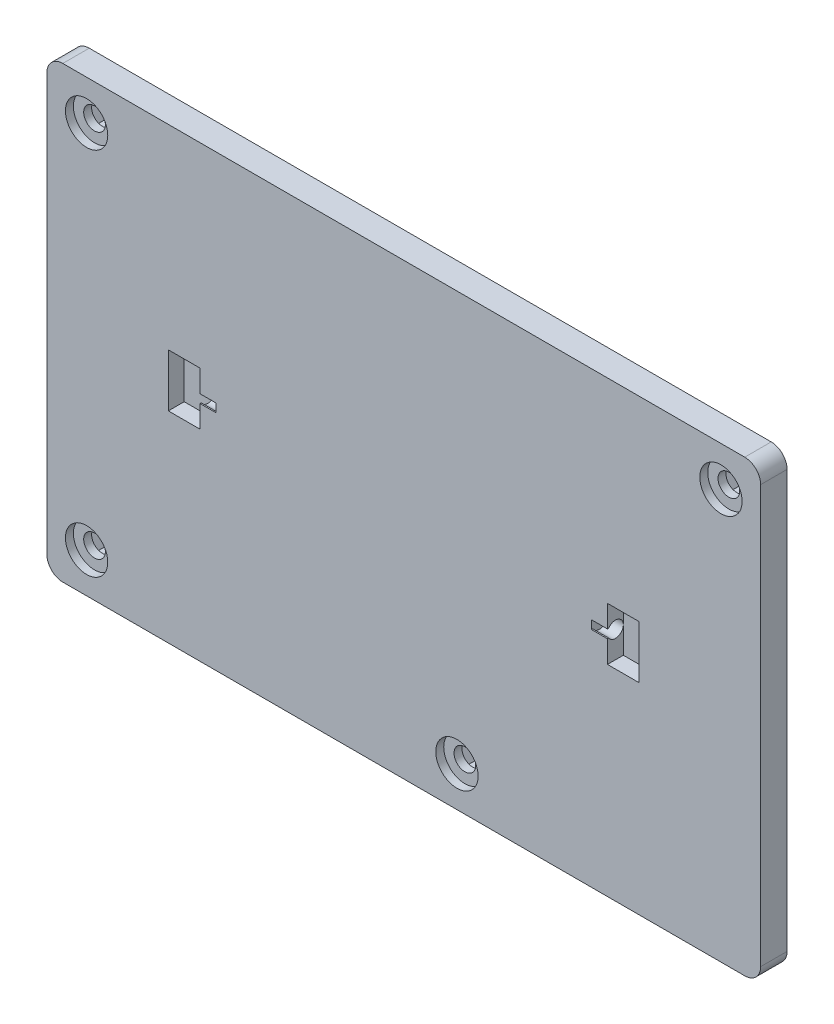
SolidWorks part; units mm, degrees
ref_plane "前视基准面" through (0, 0, 0) normal (0, 0, 1) x (1, 0, 0)
ref_plane "上视基准面" through (0, 0, 0) normal (0, 1, 0) x (1, 0, 0)
ref_plane "右视基准面" through (0, 0, 0) normal (1, 0, 0) x (0, 0, -1)
other "Configuration Table"
sketch "草图1" plane through (0, 0, 0) normal (0, 0, 1) x (1, 0, 0)
  line L1 (-64.45, 0) -> (64.45, 0)
  line L2 (-67.45, 3) -> (-67.45, 81.9)
  line L3 (-64.45, 84.9) -> (64.45, 84.9)
  line L4 (67.45, 3) -> (67.45, 81.9)
  arc A0 (-64.45, 0) -> (-67.45, 3) centre (-64.45, 3) cw
  arc A1 (64.45, 0) -> (67.45, 3) centre (64.45, 3) ccw
  arc A2 (64.45, 84.9) -> (67.45, 81.9) centre (64.45, 81.9) cw
  arc A3 (-67.45, 81.9) -> (-64.45, 84.9) centre (-64.45, 81.9) cw
  point P4 (0, 0)
  dimension "D1" = 3
extrude "凸台-拉伸1" add sketch "草图1" along normal blind 5
sketch "草图2" plane through (0, 0, 0) normal (0, 0, -1) x (-1, 0, 0)
  line L0 (-67.45, 3) -> (-67.45, 81.9) construction
  line L1 (-56.6591, 77.4) -> (-58.3046, 80.25)
  line L2 (-58.3046, 80.25) -> (-61.5954, 80.25)
  line L3 (-61.5954, 80.25) -> (-63.2409, 77.4)
  line L4 (-63.2409, 77.4) -> (-61.5954, 74.55)
  line L5 (-61.5954, 74.55) -> (-58.3046, 74.55)
  line L6 (-58.3046, 74.55) -> (-56.6591, 77.4)
  line L7 (-64.45, 84.9) -> (64.45, 84.9) construction
  line L8 (-67.45, 42.45) -> (67.45, 42.45) construction
  line L9 (67.45, 81.9) -> (67.45, 3) construction
  line L10 (0, 0) -> (0, 84.9) construction
  line L11 (64.45, 0) -> (-64.45, 0) construction
  line L12 (58.3046, 74.55) -> (56.6591, 77.4)
  line L13 (61.5954, 74.55) -> (58.3046, 74.55)
  line L14 (63.2409, 77.4) -> (61.5954, 74.55)
  line L15 (61.5954, 80.25) -> (63.2409, 77.4)
  line L16 (58.3046, 80.25) -> (61.5954, 80.25)
  line L17 (56.6591, 77.4) -> (58.3046, 80.25)
  line L30 (-13.3409, 7.5) -> (-11.6954, 4.65)
  line L31 (-11.6954, 4.65) -> (-8.4046, 4.65)
  line L32 (-8.4046, 4.65) -> (-6.7591, 7.5)
  line L33 (-6.7591, 7.5) -> (-8.4046, 10.35)
  line L34 (-8.4046, 10.35) -> (-11.6954, 10.35)
  line L35 (-11.6954, 10.35) -> (-13.3409, 7.5)
  line L36 (56.6591, 7.5) -> (58.3046, 4.65)
  line L37 (58.3046, 4.65) -> (61.5954, 4.65)
  line L38 (61.5954, 4.65) -> (63.2409, 7.5)
  line L39 (63.2409, 7.5) -> (61.5954, 10.35)
  line L40 (61.5954, 10.35) -> (58.3046, 10.35)
  line L41 (58.3046, 10.35) -> (56.6591, 7.5)
  circle A0 centre (-59.95, 77.4) radius 2.85 construction
  circle A3 centre (-10.05, 7.5) radius 2.85 construction
  circle A4 centre (59.95, 7.5) radius 2.85 construction
  dimension "D1" = 7.5
  dimension "D2" = 7.5
extrude "切除-拉伸1" cut sketch "草图2" against normal blind 2
sketch "草图3" plane through (0, 0, 2) normal (0, 0, -1) x (-1, 0, 0)
  line L0 (-61.5954, 80.25) -> (-58.3046, 74.55) construction
  line L1 (-56.6591, 77.4) -> (-59.95, 77.4) construction
  line L2 (-67.45, 42.45) -> (67.45, 42.45) construction
  line L3 (-67.45, 3) -> (-67.45, 81.9) construction
  line L4 (67.45, 81.9) -> (67.45, 3) construction
  line L5 (0, 84.9) -> (0, 0) construction
  line L6 (-64.45, 84.9) -> (64.45, 84.9) construction
  line L9 (-6.7591, 7.5) -> (-10.05, 7.5) construction
  line L10 (-8.4046, 10.35) -> (-11.6954, 4.65) construction
  circle A1 centre (-59.95, 77.4) radius 2.05
  circle A2 centre (59.95, 77.4) radius 2.05
  circle A6 centre (-10.05, 7.5) radius 2.05
  circle A7 centre (59.95, 7.5) radius 2.05
  dimension "D1" = 4.1
extrude "切除-拉伸2" cut sketch "草图3" against normal blind 3
sketch "草图4" plane through (0, 0, 5) normal (0, 0, 1) x (1, 0, 0)
  line L0 (-67.45, 81.9) -> (-67.45, 3) construction
  line L1 (-64.45, 0) -> (64.45, 0) construction
  line L2 (0, -8.4155) -> (0, 90.394) construction
  circle A0 centre (-59.95, 77.4) radius 4
  circle A1 centre (59.95, 77.4) radius 4
  circle A4 centre (-59.95, 7.5) radius 4
  circle A5 centre (10.05, 7.5) radius 4
  dimension "D1" = 8
  dimension "D2" = 8
  dimension "D3" = 8
  dimension "D4" = 8
  dimension "D5" = 70
  dimension "D6" = 7.5
  dimension "D7" = 7.5
  dimension "D8" = 7.5
extrude "切除-拉伸3" cut sketch "草图4" against normal blind 1.5
sketch "草图5" plane through (0, 0, 5) normal (0, 0, 1) x (1, 0, 0)
  line L0 (0, 84.9) -> (0, -9.6023) construction
  line L1 (-44.5, 48) -> (-38.5, 48)
  line L2 (-44.5, 48) -> (-44.5, 38)
  line L3 (-44.5, 38) -> (-38.5, 38)
  line L4 (-38.5, 48) -> (-38.5, 38)
  line L6 (-64.45, 0) -> (64.45, 0) construction
  line L7 (38.5, 48) -> (38.5, 38)
  line L8 (44.5, 38) -> (38.5, 38)
  line L9 (44.5, 48) -> (44.5, 38)
  line L10 (44.5, 48) -> (38.5, 48)
  dimension "D1" = 10
  dimension "D2" = 6
  dimension "D3" = 38.5
  dimension "D4" = 38
extrude "切除-拉伸4" cut sketch "草图5" against normal blind 3
sketch "草图6" plane through (38.5, 0, 0) normal (1, 0, 0) x (0, 0, -1)
  line L0 (-6.2696, 43) -> (0.482, 43) construction
  line L1 (-3.5, 48) -> (-3.5, 36.5367) construction
  line L2 (-4.7689, 43.8) -> (-5, 43.8)
  line L3 (-5, 42.2) -> (-5, 43.8)
  line L4 (-5, 48) -> (-5, 38)
  line L5 (-5, 38) -> (-2, 38)
  line L6 (-2, 38) -> (-2, 48)
  line L7 (-2, 48) -> (-5, 48)
  line L8 (-5, 48) -> (-5, 38) construction
  line L9 (-5, 38) -> (-2, 38) construction
  line L10 (-2, 38) -> (-2, 48) construction
  line L11 (-2, 48) -> (-5, 48) construction
  line L12 (-5, 42.2) -> (-4.7689, 42.2)
  arc A0 (-4.7689, 42.2) -> (-4.7689, 43.8) centre (-3.5, 43) ccw
  dimension "D3" = 3
  dimension "D2" = 5
  dimension "D4" = 0.8
  dimension "D1" = 0
extrude "切除-拉伸5" cut sketch "草图6" against normal blind 3
sketch "草图7" plane through (-38.5, 0, 0) normal (-1, 0, 0) x (0, 0, 1)
  line L3 (5, 43.8) -> (4.7689, 43.8)
  line L4 (5, 42.2) -> (5, 43.8)
  line L5 (4.7689, 42.2) -> (5, 42.2)
  line L6 (5, 43.8) -> (4.7689, 43.8)
  line L7 (5, 42.2) -> (5, 43.8)
  line L8 (4.7689, 42.2) -> (5, 42.2)
  arc A1 (4.7689, 43.8) -> (4.7689, 42.2) centre (3.5, 43) ccw
  arc A2 (4.7689, 43.8) -> (4.7689, 42.2) centre (3.5, 43) ccw
  dimension "D1" = 0
extrude "切除-拉伸6" cut sketch "草图7" against normal blind 3
